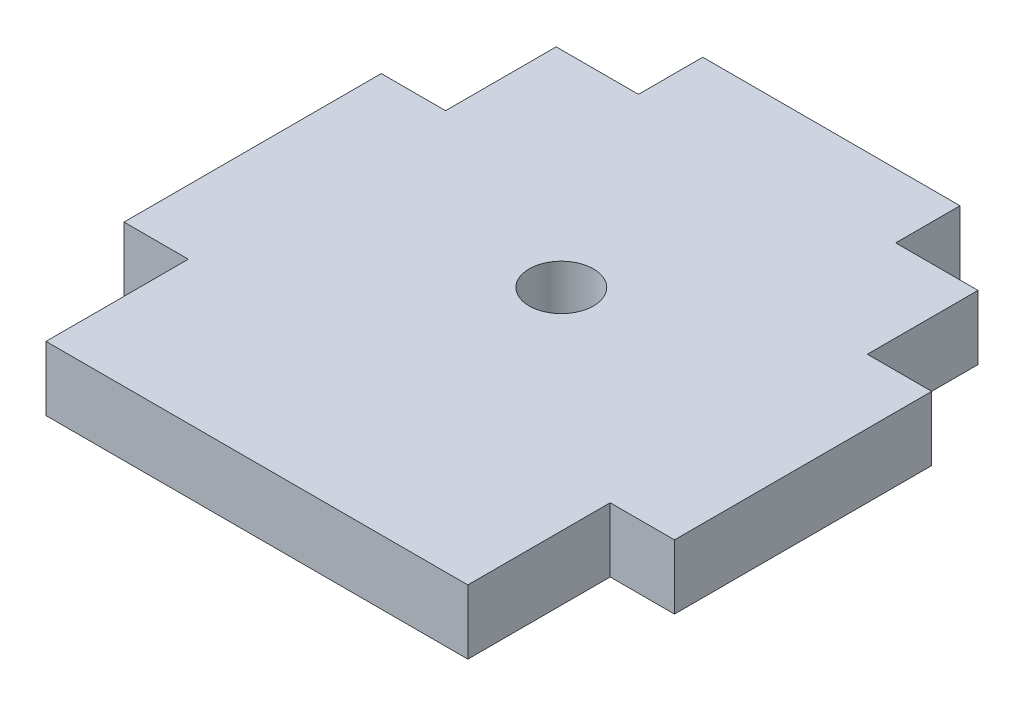
SolidWorks part; units mm, degrees
ref_plane "Front Plane" through (0, 0, 0) normal (0, 0, 1) x (1, 0, 0)
ref_plane "Top Plane" through (0, 0, 0) normal (0, 1, 0) x (1, 0, 0)
ref_plane "Right Plane" through (0, 0, 0) normal (1, 0, 0) x (0, 0, -1)
sketch "Sketch1" plane through (0, 0, 0) normal (0, 1, 0) x (1, 0, 0)
  line L0 (8.128, 50.3767) -> (8.128, 56.7267)
  line L1 (0, 0) -> (41.656, 0)
  line L2 (0, 0) -> (0, 14.0547)
  line L3 (0, 50.3767) -> (8.128, 50.3767)
  line L4 (41.656, 0) -> (41.656, 14.0547)
  line L5 (8.128, 56.7267) -> (33.528, 56.7267)
  line L6 (33.528, 56.7267) -> (33.528, 50.3767)
  line L7 (0, 39.4547) -> (0, 50.3767)
  line L8 (0, 39.4547) -> (-6.35, 39.4547)
  line L9 (33.528, 50.3767) -> (41.656, 50.3767)
  line L10 (0, 14.0547) -> (-6.35, 14.0547)
  line L11 (-6.35, 39.4547) -> (-6.35, 14.0547)
  line L12 (8.128, 50.3767) -> (33.528, 50.3767) construction
  line L13 (0, 39.4547) -> (0, 14.0547) construction
  line L15 (20.828, 30.0567) -> (20.828, 50.3767) construction
  line L16 (41.656, 14.0547) -> (48.006, 14.0547)
  line L17 (48.006, 39.4547) -> (48.006, 14.0547)
  line L18 (41.656, 39.4547) -> (48.006, 39.4547)
  line L19 (41.656, 39.4547) -> (41.656, 50.3767)
  circle A0 centre (20.828, 30.0567) radius 3.175
  dimension "D8" = 6.35
  dimension "D1" = 6.35
  dimension "D2" = 6.35
  dimension "D3" = 25.4
  dimension "D4" = 25.4
  dimension "D5" = 50.3767
  dimension "D6" = 10.922
  dimension "D7" = 41.656
  dimension "D9" = 20.32
extrude "Extrude1" add sketch "Sketch1" along normal blind 6.35
